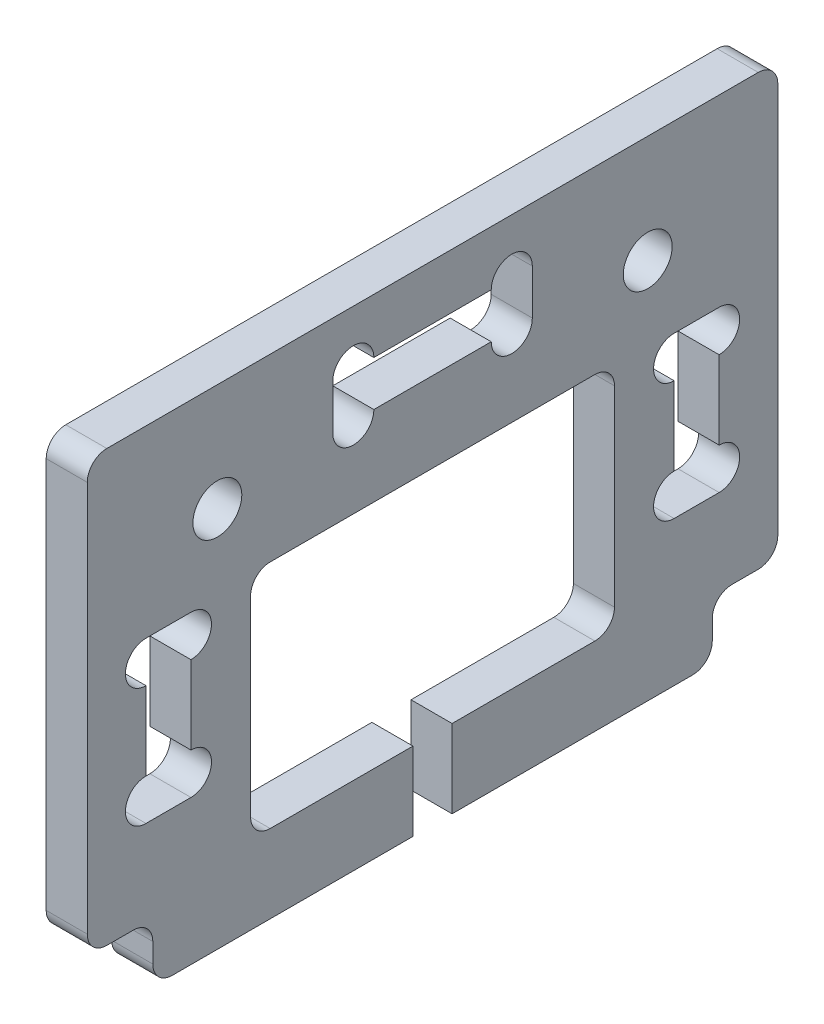
SolidWorks part; units mm, degrees
material "Thornel Mat VMA"
ref_plane "前视基准面" through (0, 0, 0) normal (0, 0, 1) x (1, 0, 0)
ref_plane "上视基准面" through (0, 0, 0) normal (0, 1, 0) x (1, 0, 0)
ref_plane "右视基准面" through (0, 0, 0) normal (1, 0, 0) x (0, 0, -1)
sketch "草图1" plane through (0, 0, 0) normal (1, 0, 0) x (0, 0, -1)
  line L0 (0, 0) -> (0, -14) construction
  line L1 (17.65, -11) -> (14.3, -11)
  line L2 (17.65, -11) -> (17.65, 11)
  line L3 (17.65, 11) -> (-17.65, 11)
  line L4 (-17.65, -11) -> (-17.65, 11)
  line L5 (17.65, -11) -> (-17.65, 11) construction
  line L6 (17.65, 11) -> (-17.65, -11) construction
  line L7 (-12.35, -6.6) -> (-14.65, -6.6)
  line L8 (-12.35, -6.6) -> (-12.35, 1.6)
  line L9 (-12.35, 1.6) -> (-14.65, 1.6)
  line L10 (-14.65, -6.6) -> (-14.65, 1.6)
  line L11 (-12.35, -6.6) -> (-14.65, 1.6) construction
  line L12 (-12.35, 1.6) -> (-14.65, -6.6) construction
  line L13 (12.35, 1.6) -> (14.65, -6.6) construction
  line L14 (12.35, -6.6) -> (14.65, 1.6) construction
  line L15 (14.65, -6.6) -> (14.65, 1.6)
  line L16 (12.35, 1.6) -> (14.65, 1.6)
  line L17 (12.35, -6.6) -> (12.35, 1.6)
  line L18 (12.35, -6.6) -> (14.65, -6.6)
  line L19 (-17.65, 5.5) -> (-9.9278, 5.5) construction
  line L20 (-14.3, -11) -> (-14.3, -14)
  line L21 (5.1, 5.9) -> (-5.1, 5.9)
  line L22 (5.1, 5.9) -> (5.1, 8.2)
  line L23 (5.1, 8.2) -> (-5.1, 8.2)
  line L24 (-5.1, 5.9) -> (-5.1, 8.2)
  line L25 (5.1, 5.9) -> (-5.1, 8.2) construction
  line L26 (5.1, 8.2) -> (-5.1, 5.9) construction
  line L27 (9.3, -10) -> (-9.3, -10)
  line L28 (9.3, -10) -> (9.3, 1.8)
  line L29 (9.3, 1.8) -> (-9.3, 1.8)
  line L30 (-9.3, -10) -> (-9.3, 1.8)
  line L31 (9.3, -10) -> (-9.3, 1.8) construction
  line L32 (9.3, 1.8) -> (-9.3, -10) construction
  line L33 (-14.3, -14) -> (14.3, -14)
  line L34 (14.3, -14) -> (14.3, -11)
  line L35 (-14.3, -11) -> (-17.65, -11)
  circle A0 centre (-12.35, 0.55) radius 1.05
  circle A1 centre (-14.65, 0.55) radius 1.05
  circle A2 centre (-14.65, -5.55) radius 1.05
  circle A3 centre (-12.35, -5.55) radius 1.05
  circle A4 centre (12.35, -5.55) radius 1.05
  circle A5 centre (14.65, -5.55) radius 1.05
  circle A6 centre (14.65, 0.55) radius 1.05
  circle A7 centre (12.35, 0.55) radius 1.05
  circle A8 centre (-11, 5.5) radius 1.25
  circle A9 centre (11, 5.5) radius 1.25
  circle A10 centre (-4.05, 8.2) radius 1.05
  circle A11 centre (4.05, 8.2) radius 1.05
  circle A12 centre (4.05, 5.9) radius 1.05
  circle A13 centre (-4.05, 5.9) radius 1.05
  point P0 (0, 0)
  point P6 (-13.5, -2.5)
  point P33 (13.5, -2.5)
  point P40 (0, 7.05)
  point P53 (0, -4.1)
  dimension "D5" = 2.1
  dimension "D10" = 2.5
  dimension "D15" = 11.8
  dimension "D1" = 2.3
  dimension "D2" = 8.2
  dimension "D3" = 13.5
  dimension "D4" = 8.5
  dimension "D6" = 27
  dimension "D7" = 3
  dimension "D8" = 8
  dimension "D9" = 22
  dimension "D11" = 2.3
  dimension "D12" = 10.2
  dimension "D13" = 9.55
  dimension "D14" = 1
  dimension "D16" = 18.6
  dimension "D17" = 3
  dimension "D18" = 5
extrude "凸台-拉伸1" add sketch "草图1" along normal blind 2.1
fillet "圆角1" radius 1 12 edges at (1.05, 11, -17.65) (1.05, -11, -17.65) (1.05, 11, 17.65) (1.05, -10, -9.3) (1.05, 1.8, -9.3) (1.05, -10, 9.3) (1.05, 1.8, 9.3) (1.05, -11, -14.3) (1.05, -14, -14.3) (1.05, -11, 17.65) (1.05, -11, 14.3) (1.05, -14, 14.3)
sketch "草图2" plane through (2.1, 0, 0) normal (1, 0, 0) x (0, 0, -1)
  line L0 (0, -10) -> (0, -12.0996) construction
  line L1 (8.3, -10) -> (-8.3, -10) construction
  line L2 (-1, -10) -> (-1, -14)
  line L3 (-13.3, -14) -> (13.3, -14) construction
  line L4 (-1, -14) -> (1, -14)
  line L5 (1, -14) -> (1, -10)
  line L6 (1, -10) -> (-1, -10)
  dimension "D1" = 2
extrude "切除-拉伸1" cut sketch "草图2" against normal blind 10
